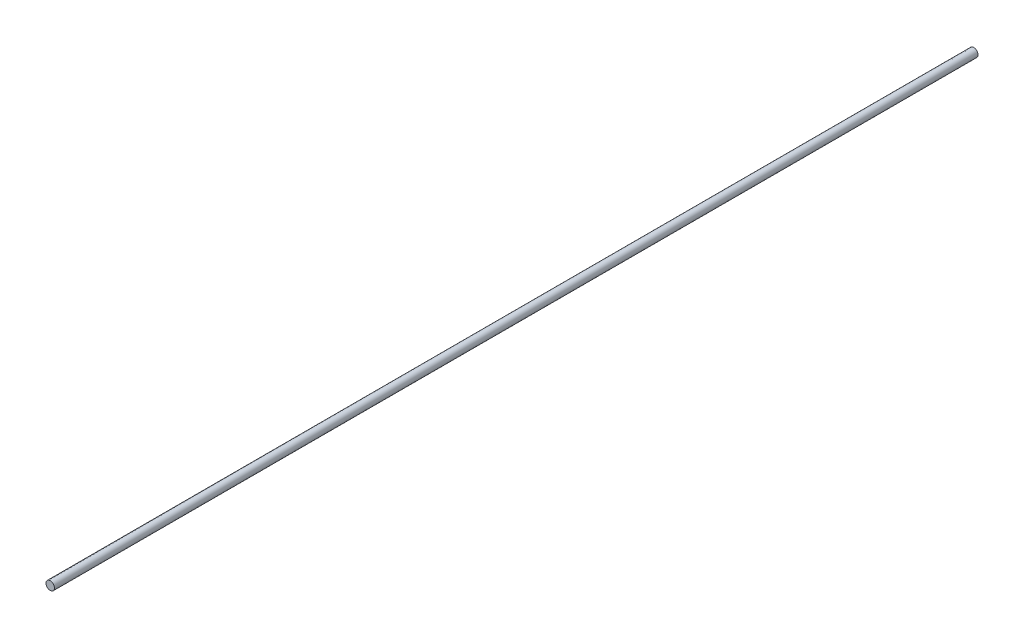
SolidWorks part; units mm, degrees
material "AISI 4340 Steel, normalized"
ref_plane "Front Plane" through (0, 0, 0) normal (0, 0, 1) x (1, 0, 0)
ref_plane "Top Plane" through (0, 0, 0) normal (0, 1, 0) x (1, 0, 0)
ref_plane "Right Plane" through (0, 0, 0) normal (1, 0, 0) x (0, 0, -1)
sketch "Sketch1" plane through (0, 0, 0) normal (0, 0, 1) x (1, 0, 0)
  circle A0 centre (0, 0) radius 1.5
extrude "Thread_Major_Envelope" add sketch "Sketch1" along normal blind 327
